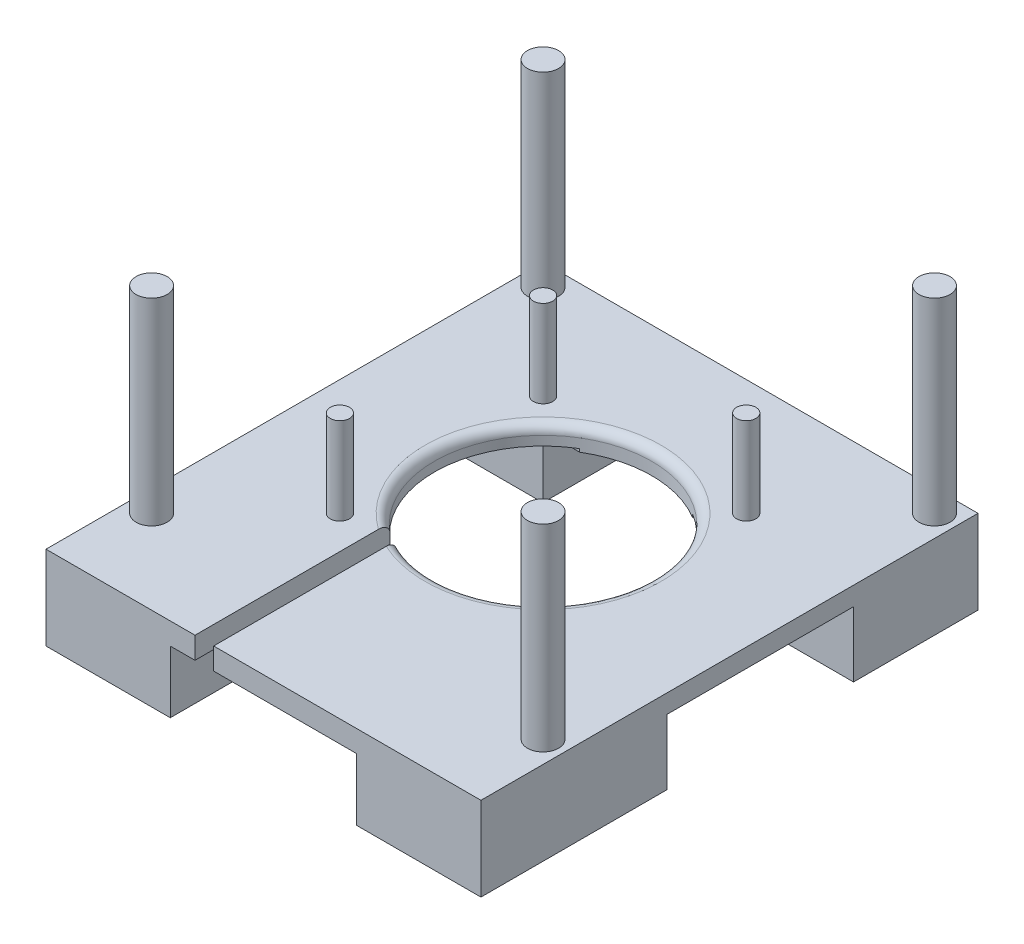
SolidWorks part; units mm, degrees
ref_plane "Front Plane" through (0, 0, 0) normal (0, 0, 1) x (1, 0, 0)
ref_plane "Top Plane" through (0, 0, 0) normal (0, 1, 0) x (1, 0, 0)
ref_plane "Right Plane" through (0, 0, 0) normal (1, 0, 0) x (0, 0, -1)
sketch "Sketch1" plane through (0, 0, 0) normal (0, 1, 0) x (1, 0, 0)
  line L1 (35, 35) -> (-35, 35)
  line L2 (35, 35) -> (35, -35)
  line L3 (35, -35) -> (-35, -35)
  line L4 (-35, 35) -> (-35, -35)
  line L5 (35, 35) -> (-35, -35) construction
  line L6 (35, -35) -> (-35, 35) construction
  point P0 (0, 0)
  dimension "D1" = 70
  dimension "D2" = 70
extrude "Boss-Extrude1" add sketch "Sketch1" along normal blind 13.5
sketch "Sketch5" plane through (0, 13.5, 0) normal (0, 1, 0) x (1, 0, 0)
  line L0 (0, 35) -> (0, -35) construction
  line L1 (35, 35) -> (-35, 35) construction
  line L2 (-35, -35) -> (35, -35) construction
  line L3 (-35, 0) -> (35, 0) construction
  line L4 (-35, 35) -> (-35, -35) construction
  line L5 (35, -35) -> (35, 35) construction
  circle A0 centre (-16.35, 16.35) radius 1.55
  circle A1 centre (16.35, 16.35) radius 1.55
  circle A2 centre (16.35, -16.35) radius 1.55
  circle A3 centre (-16.35, -16.35) radius 1.55
  dimension "D1" = 3.1
  dimension "D2" = 32.7
  dimension "D3" = 32.7
extrude "Fans_Column" add sketch "Sketch5" along normal blind 14
sketch "Sketch6" plane through (0, 13.5, 0) normal (0, 1, 0) x (1, 0, 0)
  circle A0 centre (0, 0) radius 17.5
  dimension "D1" = 35
extrude "Cut-Extrude2" cut sketch "Sketch6" against normal blind 15
fillet "Fillet1" radius 1.5 1 edges at (0, 13.5, 17.5)
sketch "Sketch7" plane through (0, 13.5, 0) normal (0, 1, 0) x (1, 0, 0)
  line L0 (0, 35) -> (0, -35) construction
  line L1 (-35, 0) -> (35, 0) construction
  line L4 (-35, 35) -> (-35, -35)
  line L5 (-35, -35) -> (35, -35)
  line L6 (35, -35) -> (35, 35)
  line L7 (35, 35) -> (-35, 35)
  line L8 (-35, 35) -> (-35, -35)
  line L9 (-35, -35) -> (35, -35)
  line L10 (35, -35) -> (35, 35)
  line L11 (35, 35) -> (-35, 35)
  circle A0 centre (-31.5, 31.5) radius 2.5
  circle A1 centre (31.5, 31.5) radius 2.5
  circle A2 centre (31.5, -31.5) radius 2.5
  circle A3 centre (-31.5, -31.5) radius 2.5
  dimension "D2" = 5
  dimension "D3" = 3.5
  dimension "D4" = 3.5
  dimension "D1" = 0
extrude "Boss-Extrude4" add sketch "Sketch7" along normal blind 31.75 contours A3 | A0 | A1 | A2
sketch "Sketch8" plane through (0, 0, 35) normal (0, 0, 1) x (1, 0, 0)
  line L0 (-35, 13.5) -> (35, 13.5) construction
  line L1 (-11.0188, 13.5) -> (-8.0188, 13.5)
  line L2 (-11.0188, 13.5) -> (-11.0188, 9.5)
  line L3 (-11.0188, 9.5) -> (-8.0188, 9.5)
  line L4 (-8.0188, 13.5) -> (-8.0188, 9.5)
  dimension "D1" = 4
  dimension "D2" = 3
extrude "Cut-Extrude3" cut sketch "Sketch8" against normal blind 22
sketch "Sketch9" plane through (0, 0, 35) normal (0, 0, 1) x (1, 0, 0)
  line L8 (-8.0188, 9.5) -> (-11.0188, 9.5)
  line L9 (-11.0188, 9.5) -> (-11.0188, 13.5)
  line L10 (-11.0188, 13.5) -> (-35, 13.5)
  line L11 (-35, 13.5) -> (-35, 0)
  line L12 (-35, 0) -> (35, 0)
  line L13 (35, 0) -> (35, 13.5)
  line L14 (35, 13.5) -> (-8.0188, 13.5)
  line L15 (-8.0188, 13.5) -> (-8.0188, 9.5)
  line L16 (-8.0188, 9.5) -> (-11.0188, 9.5)
  line L17 (-11.0188, 9.5) -> (-11.0188, 13.5)
  line L18 (-11.0188, 13.5) -> (-35, 13.5)
  line L19 (-35, 13.5) -> (-35, 0)
  line L20 (-35, 0) -> (35, 0)
  line L21 (35, 0) -> (35, 13.5)
  line L22 (35, 13.5) -> (-8.0188, 13.5)
  line L23 (-8.0188, 13.5) -> (-8.0188, 9.5)
  dimension "D1" = 0
extrude "Boss-Extrude5" add sketch "Sketch9" along normal blind 10
sketch "Sketch10" plane through (-35, 0, 0) normal (-1, 0, 0) x (0, 0, 1)
  line L0 (-35, 0) -> (45, 0) construction
  line L1 (-14.9688, 0) -> (15.0312, 0)
  line L2 (-14.9688, 0) -> (-14.9688, 10.5)
  line L3 (-14.9688, 10.5) -> (15.0312, 10.5)
  line L4 (15.0312, 0) -> (15.0312, 10.5)
  line L5 (0.0312, 10.5) -> (0.0312, 0) construction
  dimension "D1" = 30
  dimension "D2" = 10.5
extrude "Cut-Extrude4" cut sketch "Sketch10" against normal through all
sketch "Sketch11" plane through (0, 0, -35) normal (0, 0, -1) x (-1, 0, 0)
  line L0 (-35, 0) -> (35, 0) construction
  line L1 (-15, 0) -> (15, 0)
  line L2 (-15, 0) -> (-15, 10)
  line L3 (-15, 10) -> (15, 10)
  line L4 (15, 0) -> (15, 10)
  line L5 (0, 10) -> (0, 0) construction
  dimension "D1" = 10
  dimension "D2" = 30
extrude "Cut-Extrude5" cut sketch "Sketch11" against normal through all
